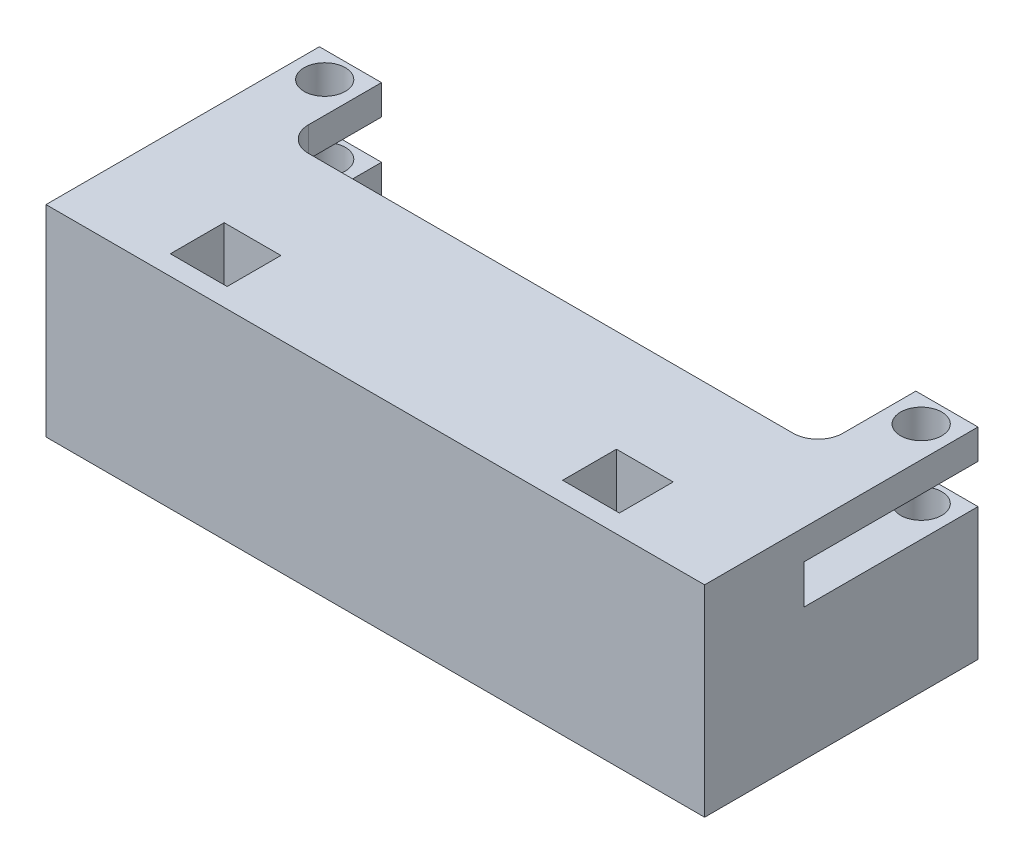
SolidWorks part; units mm, degrees
ref_plane "Front Plane" through (0, 0, 0) normal (0, 0, 1) x (1, 0, 0)
ref_plane "Top Plane" through (0, 0, 0) normal (0, 1, 0) x (1, 0, 0)
ref_plane "Right Plane" through (0, 0, 0) normal (1, 0, 0) x (0, 0, -1)
sketch "Sketch2" plane through (0, 0, 0) normal (0, 1, 0) x (1, 0, 0)
  line L0 (-33.655, 13.97) -> (-27.305, 13.97)
  line L1 (-33.655, -13.97) -> (33.655, -13.97)
  line L2 (-33.655, -13.97) -> (-33.655, 13.97)
  line L4 (33.655, -13.97) -> (33.655, 13.97)
  line L5 (-33.655, -13.97) -> (33.655, 13.97) construction
  line L6 (-33.655, 13.97) -> (33.655, -13.97) construction
  line L7 (33.655, 13.97) -> (27.305, 13.97)
  line L8 (-27.305, 13.97) -> (-27.305, 6.51)
  line L9 (-24.765, 3.97) -> (24.765, 3.97)
  line L10 (27.305, 6.51) -> (27.305, 13.97)
  arc A0 (24.765, 3.97) -> (27.305, 6.51) centre (24.765, 6.51) ccw
  arc A1 (-27.305, 6.51) -> (-24.765, 3.97) centre (-24.765, 6.51) ccw
  point P0 (0, 0)
  dimension "D5" = 2.54
  dimension "D1" = 67.31
  dimension "D2" = 27.94
  dimension "D3" = 6.35
  dimension "D4" = 6.35
  dimension "D6" = 10
extrude "Boss-Extrude1" add sketch "Sketch2" along normal blind 20.574
sketch "Sketch3" plane through (0, 0, 0) normal (0, 0, 1) x (1, 0, 0)
  line L6 (-33.655, 20.574) -> (-33.655, 0) construction
  line L7 (-33.655, 13.526) -> (33.655, 13.526)
  line L8 (-33.655, 13.526) -> (-33.655, 17.526)
  line L9 (-33.655, 17.526) -> (33.655, 17.526)
  line L10 (33.655, 13.526) -> (33.655, 17.526)
  line L11 (33.655, 20.574) -> (33.655, 0) construction
  line L12 (-33.655, 20.574) -> (33.655, 20.574) construction
  line L13 (-33.655, 0) -> (33.655, 0) construction
  dimension "D1" = 4
  dimension "D2" = 3.048
  dimension "D3" = 13.526
extrude "Cut-Extrude1" cut sketch "Sketch3" against normal blind 14.224 and the other way blind 3.81
sketch "Sketch4" plane through (0, 20.574, 0) normal (0, 1, 0) x (1, 0, 0)
  circle A0 centre (-30.48, 11.3377) radius 2.1056
  circle A1 centre (30.48, 11.3377) radius 2.1056
extrude "Cut-Extrude2" cut sketch "Sketch4" against normal through all
sketch "Sketch6" plane through (0, 20.574, 0) normal (0, 1, 0) x (1, 0, 0)
  line L0 (0, 3.97) -> (0, -13.97) construction
  line L1 (24.765, 3.97) -> (-24.765, 3.97) construction
  line L2 (-33.655, -13.97) -> (33.655, -13.97) construction
  line L20 (17.145, -11.97) -> (17.145, -6.47)
  line L21 (17.145, -11.97) -> (22.945, -11.97)
  line L22 (22.945, -11.97) -> (22.945, -6.47)
  line L23 (17.145, -6.47) -> (22.945, -6.47)
  line L24 (-22.945, -11.97) -> (-22.945, -6.47)
  line L25 (-22.945, -11.97) -> (-17.145, -11.97)
  line L26 (-17.145, -11.97) -> (-17.145, -6.47)
  line L27 (-22.945, -6.47) -> (-17.145, -6.47)
  point P6 (-17.145, -9.22)
  dimension "D1" = 2
  dimension "D2" = 5.8
  dimension "D3" = 5.5
  dimension "D4" = 5.5
  dimension "D5" = 5.8
extrude "Cut-Extrude3" cut sketch "Sketch6" against normal through all
